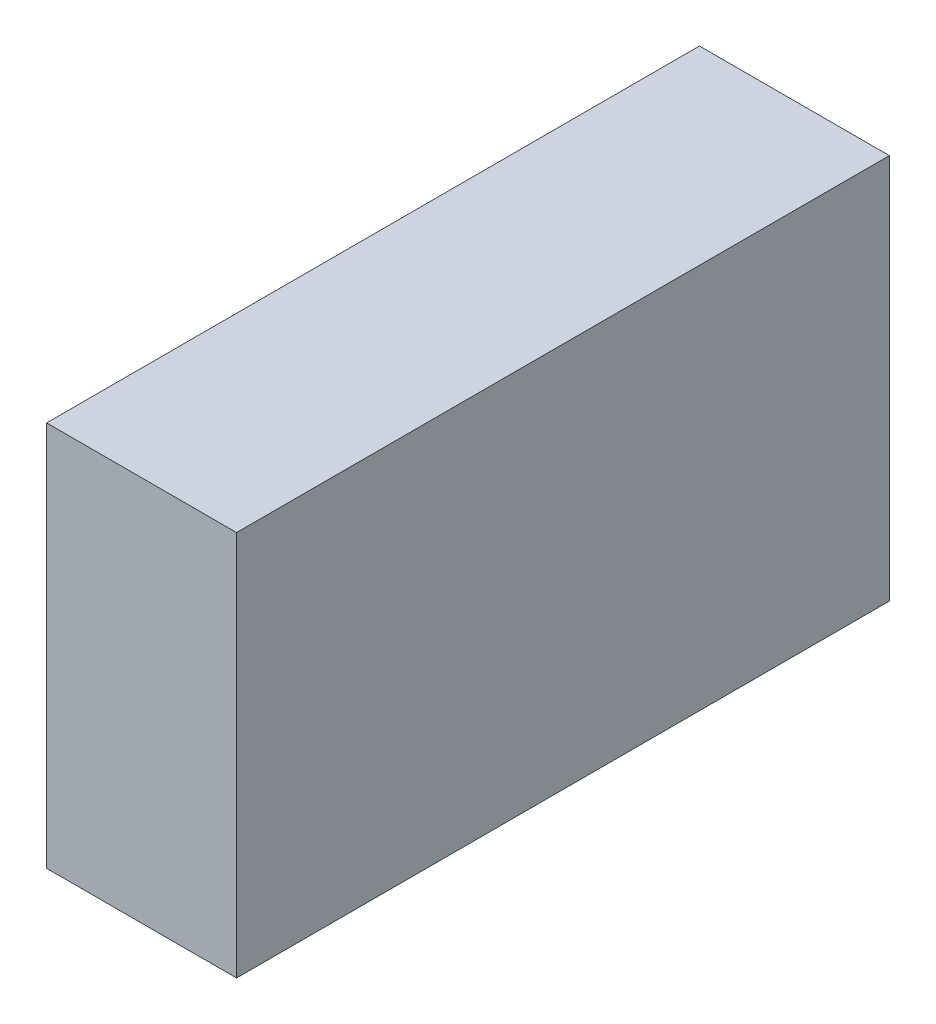
SolidWorks part; units mm, degrees
ref_plane "Front Plane" through (0, 0, 0) normal (0, 0, 1) x (1, 0, 0)
ref_plane "Top Plane" through (0, 0, 0) normal (0, 1, 0) x (1, 0, 0)
ref_plane "Right Plane" through (0, 0, 0) normal (1, 0, 0) x (0, 0, -1)
sketch "草圖1" plane through (0, 0, 0) normal (0, 0, 1) x (1, 0, 0)
  line L0 (-16, -32.5) -> (16, -32.5)
  line L1 (16, -32.5) -> (16, 32.5)
  line L2 (16, 32.5) -> (-16, 32.5)
  line L3 (-16, 32.5) -> (-16, -32.5)
extrude "填料-伸長1" add sketch "草圖1" along normal blind 110
